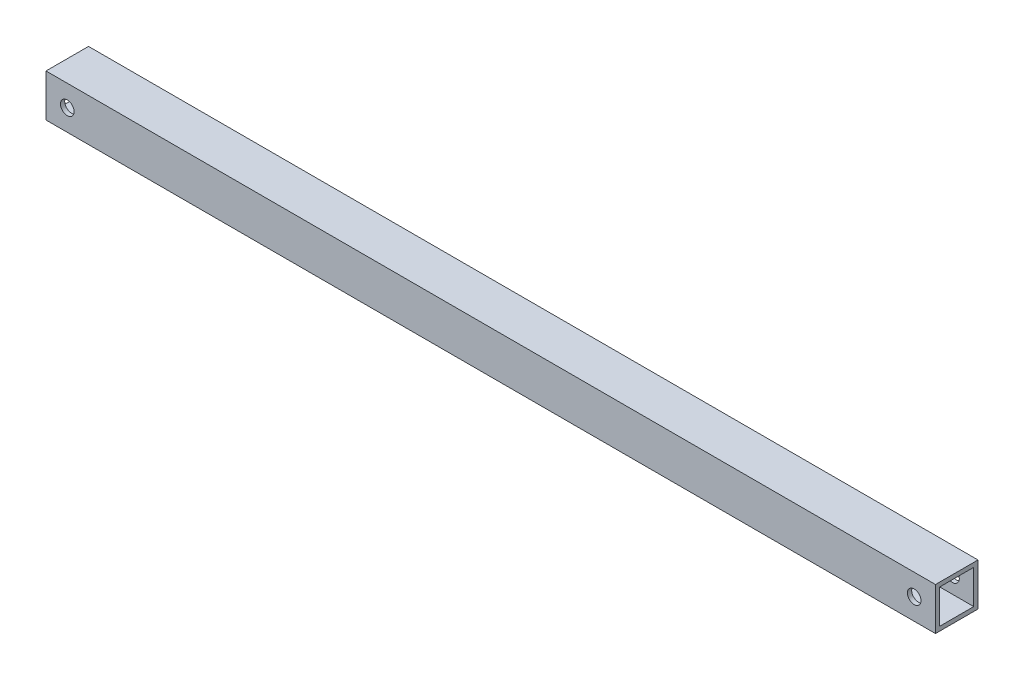
SolidWorks part; units mm, degrees
ref_plane "正面" through (0, 0, 0) normal (0, 0, 1) x (1, 0, 0)
ref_plane "平面" through (0, 0, 0) normal (0, 1, 0) x (1, 0, 0)
ref_plane "右側面" through (0, 0, 0) normal (1, 0, 0) x (0, 0, -1)
sketch "ｽｹｯﾁ1" plane through (0, 0, 0) normal (0, 0, 1) x (1, 0, 0)
  line L1 (-363.1089, 240) -> (-572.2947, 240)
  line L2 (-363.1089, 240) -> (-363.1089, 250)
  line L3 (-363.1089, 250) -> (-572.2947, 250)
  line L4 (-572.2947, 240) -> (-572.2947, 250)
  circle A0 centre (-368.1089, 245) radius 1.6
  circle A1 centre (-567.2947, 245) radius 1.6
  dimension "D1" = 5
extrude "ﾎﾞｽ - 押し出し1" add sketch "ｽｹｯﾁ1" along normal blind 10
sketch "ｽｹｯﾁ2" plane through (-572.2947, 0, 0) normal (-1, 0, 0) x (0, 0, 1)
  line L0 (10, 240) -> (0, 240) construction
  line L1 (1, 241) -> (9, 241)
  line L2 (1, 241) -> (1, 249)
  line L3 (1, 249) -> (9, 249)
  line L4 (9, 241) -> (9, 249)
  line L5 (0, 250) -> (0, 240) construction
  point P4 (0, 0)
  dimension "D1" = 1
  dimension "D2" = 8
  dimension "D3" = 8
  dimension "D4" = 1
extrude "ｶｯﾄ - 押し出し1" cut sketch "ｽｹｯﾁ2" against normal through all
